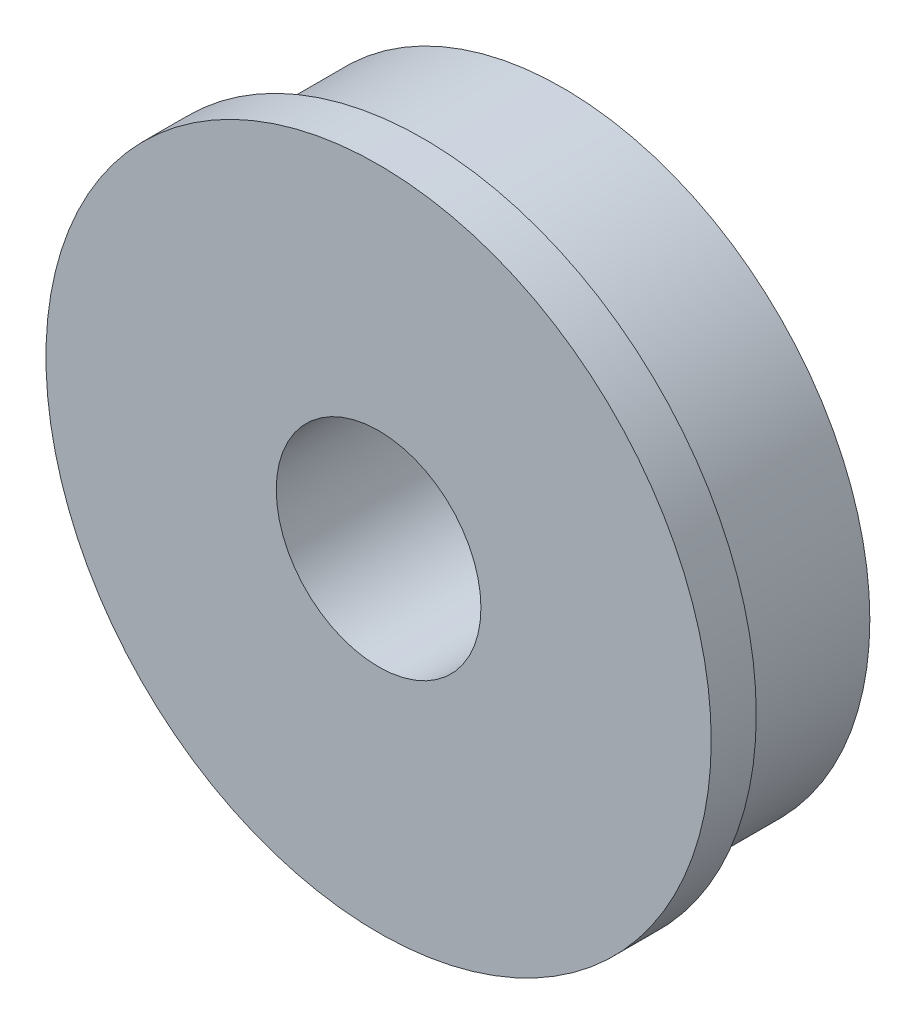
SolidWorks part; units mm, degrees
material "黄铜"
ref_plane "前视基准面" through (0, 0, 0) normal (0, 0, 1) x (1, 0, 0)
ref_plane "上视基准面" through (0, 0, 0) normal (0, 1, 0) x (1, 0, 0)
ref_plane "右视基准面" through (0, 0, 0) normal (1, 0, 0) x (0, 0, -1)
sketch "草图1" plane through (0, 0, 0) normal (0, 0, 1) x (1, 0, 0)
  circle A0 centre (0, 0) radius 5
  circle A1 centre (0, 0) radius 15
extrude "凸台-拉伸1" add sketch "草图1" along normal blind 6.8
sketch "草图2" plane through (0, 0, 6.8) normal (0, 0, 1) x (1, 0, 0)
  circle A0 centre (0, 0) radius 5
  circle A1 centre (0, 0) radius 16.25
extrude "凸台-拉伸2" add sketch "草图2" along normal blind 2.2
